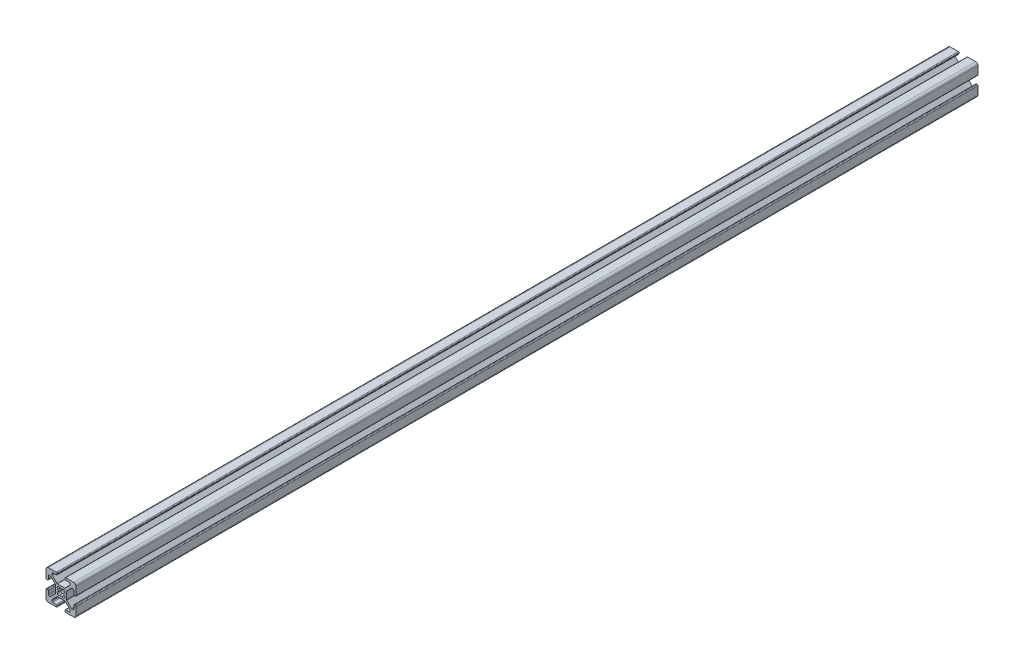
SolidWorks part; units mm, degrees
ref_plane "Front Plane" through (0, 0, 0) normal (0, 0, 1) x (1, 0, 0)
ref_plane "Top Plane" through (0, 0, 0) normal (0, 1, 0) x (1, 0, 0)
ref_plane "Right Plane" through (0, 0, 0) normal (1, 0, 0) x (0, 0, -1)
sketch "Sketch1" plane through (0, 0, 0) normal (0, 0, 1) x (1, 0, 0)
  line L0 (-5.0323, -0.3411) -> (-5.5163, -0.3411)
  line L1 (-6.0243, 0.1669) -> (-6.0243, 2.5159)
  line L2 (-4.5243, 0.1669) -> (-4.5243, 5.5289)
  line L3 (-10.8693, -5.355) -> (-10.8693, -0.5871)
  line L4 (-7.2582, 3.0239) -> (-6.5323, 3.0239)
  line L5 (-7.6174, 2.8752) -> (-10.7205, -0.2279)
  line L6 (-5.0323, -5.6011) -> (-5.5163, -5.6011)
  line L7 (-4.5243, -6.1091) -> (-4.5243, -11.4711)
  line L8 (-6.0243, -6.1091) -> (-6.0243, -8.4581)
  line L9 (-7.2582, -8.9661) -> (-6.5323, -8.9661)
  line L10 (-7.6174, -8.8173) -> (-10.7205, -5.7142)
  line L11 (-12.3994, -5.2756) -> (-12.2198, -5.096)
  line L12 (-17.1543, 6.5209) -> (-17.1543, 6.0369)
  line L13 (-17.6623, 7.0289) -> (-23.0243, 7.0289)
  line L14 (-17.6623, 5.5289) -> (-20.0113, 5.5289)
  line L15 (-12.1404, 0.6839) -> (-16.9082, 0.6839)
  line L16 (-20.5193, 4.295) -> (-20.5193, 5.0209)
  line L17 (-20.3705, 3.9358) -> (-17.2674, 0.8327)
  line L18 (-11.8943, 6.5209) -> (-11.8943, 6.0369)
  line L19 (-11.3863, 7.0289) -> (-6.0243, 7.0289)
  line L20 (-11.3863, 5.5289) -> (-9.0373, 5.5289)
  line L21 (-8.5293, 4.295) -> (-8.5293, 5.0209)
  line L22 (-8.6781, 3.9358) -> (-11.7812, 0.8327)
  line L23 (-12.2198, -0.8462) -> (-12.3994, -0.6666)
  line L24 (-24.0163, -5.6011) -> (-23.5323, -5.6011)
  line L25 (-24.5243, -6.1091) -> (-24.5243, -11.4711)
  line L26 (-23.0243, -6.1091) -> (-23.0243, -8.4581)
  line L27 (-18.1793, -0.5871) -> (-18.1793, -5.355)
  line L28 (-21.7904, -8.9661) -> (-22.5163, -8.9661)
  line L29 (-21.4312, -8.8173) -> (-18.3281, -5.7142)
  line L30 (-24.0163, -0.3411) -> (-23.5323, -0.3411)
  line L31 (-24.5243, 0.1669) -> (-24.5243, 5.5289)
  line L32 (-23.0243, 0.1669) -> (-23.0243, 2.5159)
  line L33 (-21.7904, 3.0239) -> (-22.5163, 3.0239)
  line L34 (-21.4312, 2.8752) -> (-18.3281, -0.2279)
  line L35 (-16.6492, -0.6666) -> (-16.8288, -0.8462)
  line L36 (-11.8943, -12.4631) -> (-11.8943, -11.9791)
  line L37 (-11.3863, -12.9711) -> (-6.0243, -12.9711)
  line L38 (-11.3863, -11.4711) -> (-9.0373, -11.4711)
  line L39 (-16.9082, -6.6261) -> (-12.1404, -6.6261)
  line L40 (-8.5293, -10.2371) -> (-8.5293, -10.9631)
  line L41 (-8.6781, -9.8779) -> (-11.7812, -6.7748)
  line L42 (-17.1543, -12.4631) -> (-17.1543, -11.9791)
  line L43 (-17.6623, -12.9711) -> (-23.0243, -12.9711)
  line L44 (-17.6623, -11.4711) -> (-20.0113, -11.4711)
  line L45 (-20.5193, -10.2371) -> (-20.5193, -10.9631)
  line L46 (-20.3705, -9.8779) -> (-17.2674, -6.7748)
  line L47 (-16.8288, -5.096) -> (-16.6492, -5.2756)
  arc A0 (-15.3283, -4.9062) -> (-13.7203, -4.9062) centre (-14.5243, -2.9711) ccw
  arc A1 (-6.0243, 2.5159) -> (-6.5323, 3.0239) centre (-6.5323, 2.5159) ccw
  arc A2 (-7.2582, 3.0239) -> (-7.6174, 2.8752) centre (-7.2582, 2.5159) ccw
  arc A3 (-10.7205, -0.2279) -> (-10.8693, -0.5871) centre (-10.3613, -0.5871) ccw
  arc A4 (-10.8693, -5.355) -> (-10.7205, -5.7142) centre (-10.3613, -5.355) ccw
  arc A5 (-7.6174, -8.8173) -> (-7.2582, -8.9661) centre (-7.2582, -8.4581) ccw
  arc A6 (-6.5323, -8.9661) -> (-6.0243, -8.4581) centre (-6.5323, -8.4581) ccw
  arc A7 (-5.5163, -5.6011) -> (-6.0243, -6.1091) centre (-5.5163, -6.1091) ccw
  arc A8 (-4.5243, -6.1091) -> (-5.0323, -5.6011) centre (-5.0323, -6.1091) ccw
  arc A9 (-5.0323, -0.3411) -> (-4.5243, 0.1669) centre (-5.0323, 0.1669) ccw
  arc A10 (-6.0243, 0.1669) -> (-5.5163, -0.3411) centre (-5.5163, 0.1669) ccw
  arc A11 (-13.7203, -4.9062) -> (-12.3994, -5.2756) centre (-12.9559, -4.7191) ccw
  arc A12 (-12.2198, -5.096) -> (-12.5892, -3.775) centre (-12.7763, -4.5395) ccw
  arc A13 (-17.1543, 6.5209) -> (-17.6623, 7.0289) centre (-17.6623, 6.5209) ccw
  arc A14 (-17.6623, 5.5289) -> (-17.1543, 6.0369) centre (-17.6623, 6.0369) ccw
  arc A15 (-12.5892, -3.775) -> (-12.5892, -2.1671) centre (-14.5243, -2.9711) ccw
  arc A16 (-17.2674, 0.8327) -> (-16.9082, 0.6839) centre (-16.9082, 1.1919) ccw
  arc A17 (-20.0113, 5.5289) -> (-20.5193, 5.0209) centre (-20.0113, 5.0209) ccw
  arc A18 (-20.5193, 4.295) -> (-20.3705, 3.9358) centre (-20.0113, 4.295) ccw
  arc A19 (-11.8943, 6.0369) -> (-11.3863, 5.5289) centre (-11.3863, 6.0369) ccw
  arc A20 (-11.3863, 7.0289) -> (-11.8943, 6.5209) centre (-11.3863, 6.5209) ccw
  arc A21 (-8.5293, 5.0209) -> (-9.0373, 5.5289) centre (-9.0373, 5.0209) ccw
  arc A22 (-8.6781, 3.9358) -> (-8.5293, 4.295) centre (-9.0373, 4.295) ccw
  arc A23 (-12.1404, 0.6839) -> (-11.7812, 0.8327) centre (-12.1404, 1.1919) ccw
  arc A24 (-12.5892, -2.1671) -> (-12.2198, -0.8462) centre (-12.7763, -1.4027) ccw
  arc A25 (-12.3994, -0.6666) -> (-13.7203, -1.0359) centre (-12.9559, -1.223) ccw
  arc A26 (-24.0163, -5.6011) -> (-24.5243, -6.1091) centre (-24.0163, -6.1091) ccw
  arc A27 (-23.0243, -6.1091) -> (-23.5323, -5.6011) centre (-23.5323, -6.1091) ccw
  arc A28 (-13.7203, -1.0359) -> (-15.3283, -1.0359) centre (-14.5243, -2.9711) ccw
  arc A29 (-18.3281, -5.7142) -> (-18.1793, -5.355) centre (-18.6873, -5.355) ccw
  arc A30 (-23.0243, -8.4581) -> (-22.5163, -8.9661) centre (-22.5163, -8.4581) ccw
  arc A31 (-21.7904, -8.9661) -> (-21.4312, -8.8173) centre (-21.7904, -8.4581) ccw
  arc A32 (-23.5323, -0.3411) -> (-23.0243, 0.1669) centre (-23.5323, 0.1669) ccw
  arc A33 (-24.5243, 0.1669) -> (-24.0163, -0.3411) centre (-24.0163, 0.1669) ccw
  arc A34 (-22.5163, 3.0239) -> (-23.0243, 2.5159) centre (-22.5163, 2.5159) ccw
  arc A35 (-21.4312, 2.8752) -> (-21.7904, 3.0239) centre (-21.7904, 2.5159) ccw
  arc A36 (-18.1793, -0.5871) -> (-18.3281, -0.2279) centre (-18.6873, -0.5871) ccw
  arc A37 (-15.3283, -1.0359) -> (-16.6492, -0.6666) centre (-16.0927, -1.223) ccw
  arc A38 (-16.8288, -0.8462) -> (-16.4594, -2.1671) centre (-16.2723, -1.4027) ccw
  arc A39 (-11.8943, -12.4631) -> (-11.3863, -12.9711) centre (-11.3863, -12.4631) ccw
  arc A40 (-11.3863, -11.4711) -> (-11.8943, -11.9791) centre (-11.3863, -11.9791) ccw
  arc A41 (-16.4594, -2.1671) -> (-16.4594, -3.775) centre (-14.5243, -2.9711) ccw
  arc A42 (-11.7812, -6.7748) -> (-12.1404, -6.6261) centre (-12.1404, -7.1341) ccw
  arc A43 (-9.0373, -11.4711) -> (-8.5293, -10.9631) centre (-9.0373, -10.9631) ccw
  arc A44 (-8.5293, -10.2371) -> (-8.6781, -9.8779) centre (-9.0373, -10.2371) ccw
  arc A45 (-17.1543, -11.9791) -> (-17.6623, -11.4711) centre (-17.6623, -11.9791) ccw
  arc A46 (-17.6623, -12.9711) -> (-17.1543, -12.4631) centre (-17.6623, -12.4631) ccw
  arc A47 (-20.5193, -10.9631) -> (-20.0113, -11.4711) centre (-20.0113, -10.9631) ccw
  arc A48 (-20.3705, -9.8779) -> (-20.5193, -10.2371) centre (-20.0113, -10.2371) ccw
  arc A49 (-16.9082, -6.6261) -> (-17.2674, -6.7748) centre (-16.9082, -7.1341) ccw
  arc A50 (-16.4594, -3.775) -> (-16.8288, -5.096) centre (-16.2723, -4.5395) ccw
  arc A51 (-16.6492, -5.2756) -> (-15.3283, -4.9062) centre (-16.0927, -4.7191) ccw
  arc A52 (-4.5243, 5.5289) -> (-6.0243, 7.0289) centre (-6.0243, 5.5289) ccw
  arc A53 (-6.0243, -12.9711) -> (-4.5243, -11.4711) centre (-6.0243, -11.4711) ccw
  arc A54 (-24.5243, -11.4711) -> (-23.0243, -12.9711) centre (-23.0243, -11.4711) ccw
  arc A55 (-23.0243, 7.0289) -> (-24.5243, 5.5289) centre (-23.0243, 5.5289) ccw
extrude "Extrude1" add sketch "Sketch1" along normal blind 600
